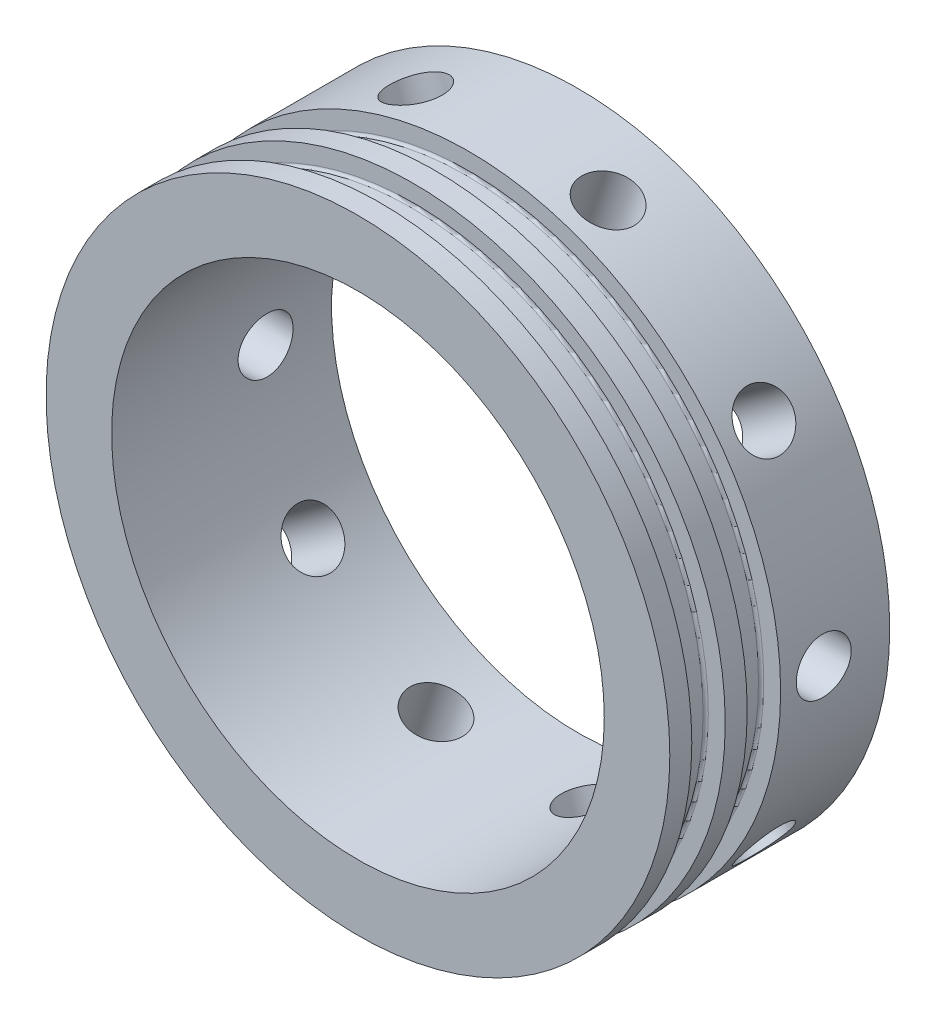
SolidWorks part; units mm, degrees
material "6061 Alloy"
ref_plane "Front Plane" through (0, 0, 0) normal (0, 0, 1) x (1, 0, 0)
ref_plane "Top Plane" through (0, 0, 0) normal (0, 1, 0) x (1, 0, 0)
ref_plane "Right Plane" through (0, 0, 0) normal (1, 0, 0) x (0, 0, -1)
sketch "Sketch1" plane through (0, 0, 0) normal (0, 0, 1) x (1, 0, 0)
  circle A0 centre (0, 0) radius 35.56
  circle A1 centre (0, 0) radius 45.0215
extrude "Boss-Extrude1" add sketch "Sketch1" along normal blind 31.75
ref_plane "Plane1" through (45.0215, 0, 0) normal (1, 0, 0) x (0, 0, -1)
sketch "Sketch2" plane through (45.0215, 0, 0) normal (1, 0, 0) x (0, 0, -1)
  line L0 (0, 0) -> (-9.525, 0)
  line L1 (-31.75, 0) -> (0, 0) construction
hole_wizard "3/8-16 Tapped Hole1" positions "Sketch4" profile "Sketch3" tap size "3/8-16" standard "ANSI Inch"
sketch "Sketch4" plane through (45.0215, 0, 0) normal (1, 0, 0) x (0, 0, -1)
  point P0 (-9.525, 0)
sketch "Sketch3" plane through (45.0215, 0, 9.525) normal (0, 1, 0) x (0, 0, -1)
  line L0 (0, 0) -> (0, 94.6932)
  line L1 (0, 94.6932) -> (3.9687, 94.6932)
  line L2 (3.9687, 94.6932) -> (3.9687, 0)
  line L5 (3.9687, 0) -> (0, 0)
  line L11 (0, -6.35) -> (0, 107.95) construction
  dimension "Thru Tap Drill Dia." = 7.9375
  dimension "Thru Tap Drill Depth" = 94.6932
cosmetic thread "Hole Thread4" parameters "D1"=9.7472, "D2"=9.525
pattern_circular "CirPattern1" count 10 over 360 about axis through (0, 0, 31.75) along (0, 0, -1) of "3/8-16 Tapped Hole1"
sketch "Sketch5" plane through (0, 0, 0) normal (1, 0, 0) x (0, 0, -1)
  line L0 (-31.75, 45.0215) -> (-28.575, 45.0215)
  line L1 (0, 45.0215) -> (-31.75, 45.0215) construction
  line L2 (-28.575, 45.0215) -> (-28.575, 42.5831)
  line L3 (-28.575, 0) -> (-28.575, 42.2021)
  line L4 (-31.75, 0) -> (0, 0) construction
  line L5 (-28.194, 42.2021) -> (-24.13, 42.2021)
  line L6 (-23.749, 42.5831) -> (-23.749, 45.0215)
  line L7 (-23.749, 45.0215) -> (-20.574, 45.0215)
  line L8 (-20.574, 45.0215) -> (-20.574, 42.5831)
  line L9 (-20.193, 42.2021) -> (-16.129, 42.2021)
  line L10 (-15.748, 42.5831) -> (-15.748, 45.0215)
  line L11 (-15.748, 45.0215) -> (-20.574, 45.0215)
  line L12 (-28.575, 45.0215) -> (-23.749, 45.0215)
  arc A0 (-15.748, 42.5831) -> (-16.129, 42.2021) centre (-16.129, 42.5831) cw
  arc A1 (-20.193, 42.2021) -> (-20.574, 42.5831) centre (-20.193, 42.5831) cw
  arc A2 (-23.749, 42.5831) -> (-24.13, 42.2021) centre (-24.13, 42.5831) cw
  arc A3 (-28.194, 42.2021) -> (-28.575, 42.5831) centre (-28.194, 42.5831) cw
  dimension "D1" = 0.381
revolve "Cut-Revolve1" cut sketch "Sketch5" angle 360 about axis through (0, 0, 31.75) along (0, 0, -1)
